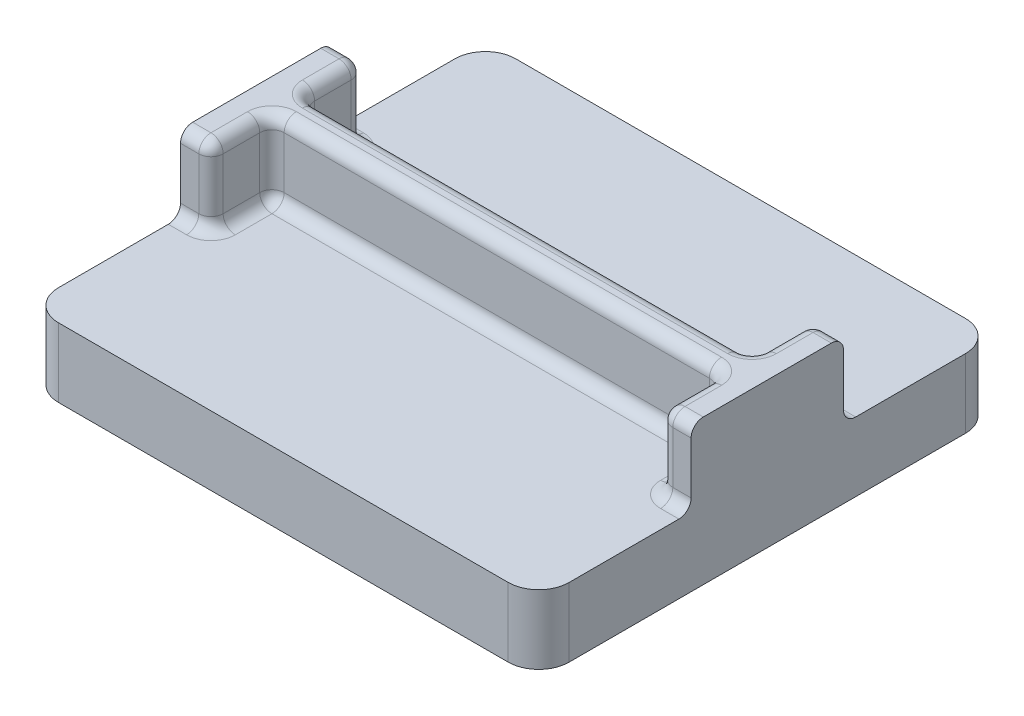
SolidWorks part; units mm, degrees
ref_plane "Front Plane" through (0, 0, 0) normal (0, 0, 1) x (1, 0, 0)
ref_plane "Top Plane" through (0, 0, 0) normal (0, 1, 0) x (1, 0, 0)
ref_plane "Right Plane" through (0, 0, 0) normal (1, 0, 0) x (0, 0, -1)
sketch "Sketch1" plane through (0, 0, 0) normal (0, 1, 0) x (1, 0, 0)
  line L1 (-16.75, -15) -> (16.75, -15)
  line L2 (-16.75, -15) -> (-16.75, 15)
  line L3 (-16.75, 15) -> (16.75, 15)
  line L4 (16.75, -15) -> (16.75, 15)
  line L5 (-16.75, -15) -> (16.75, 15) construction
  line L6 (-16.75, 15) -> (16.75, -15) construction
  point P0 (0, 0)
  dimension "D1" = 30
  dimension "D2" = 33.5
extrude "Boss-Extrude1" add sketch "Sketch1" along normal blind 4.53
sketch "Sketch2" plane through (0, 4.53, 0) normal (0, 1, 0) x (1, 0, 0)
  line L0 (-16.75, 5) -> (-14.75, 5)
  line L1 (-14.75, 5) -> (-14.75, 1)
  line L2 (-14.75, 1) -> (14.75, 1)
  line L3 (14.75, 1) -> (14.75, 5)
  line L4 (16.75, -15) -> (16.75, 15)
  line L5 (16.75, 15) -> (-16.75, 15)
  line L6 (-16.75, 15) -> (-16.75, -15)
  line L7 (-16.75, -15) -> (16.75, -15)
  line L8 (16.75, -15) -> (16.75, 15)
  line L9 (16.75, 15) -> (-16.75, 15)
  line L10 (-16.75, 15) -> (-16.75, -15)
  line L11 (-16.75, -15) -> (16.75, -15)
  line L12 (14.75, 5) -> (16.75, 5)
  line L13 (-16.75, -5) -> (-14.75, -5)
  line L14 (-14.75, -5) -> (-14.75, -1)
  line L15 (-14.75, -1) -> (14.75, -1)
  line L16 (14.75, -1) -> (14.75, -5)
  line L17 (14.75, -5) -> (16.75, -5)
  line L18 (-16.75, 5) -> (-16.75, -5)
  line M13 (-16.75, 15) -> (-16.75, -15)
  dimension "D2" = 29.5
  dimension "D4" = 2
  dimension "D5" = 2
  dimension "D6" = 10
  dimension "D7" = 4
  dimension "D8" = 10
  dimension "D1" = 0
extrude "Boss-Extrude2" add sketch "Sketch2" along normal blind 5 contours L16 L17 L8 L12 L3 L2 L1 L0 L13 L14 L15 M13
fillet "Fillet1" radius 2 4 edges at (16.75, 2.265, 15) (16.75, 2.265, -15) (-16.75, 2.265, -15) (-16.75, 2.265, 15)
fillet "Fillet3" radius 0.8 28 edges at (15.75, 4.53, 5) (15.75, 4.53, -5) (-15.75, 4.53, -5) (-15.75, 4.53, 5) (0, 9.53, 1) (0, 4.53, 1) (0, 9.53, -1) (0, 4.53, -1) (14.75, 7.03, 1) (14.75, 9.53, 3) (14.75, 7.03, 5) (14.75, 4.53, 3) (14.75, 7.03, -5) (14.75, 9.53, -3) (14.75, 7.03, -1) (14.75, 4.53, -3) (-14.75, 7.03, -1) (-14.75, 9.53, -3) (-14.75, 7.03, -5) (-14.75, 4.53, -3) (-14.75, 7.03, 5) (-14.75, 9.53, 3) (-14.75, 7.03, 1) (-14.75, 4.53, 3) (-15.75, 9.53, -5) (-15.75, 9.53, 5) (15.75, 9.53, 5) (15.75, 9.53, -5)
